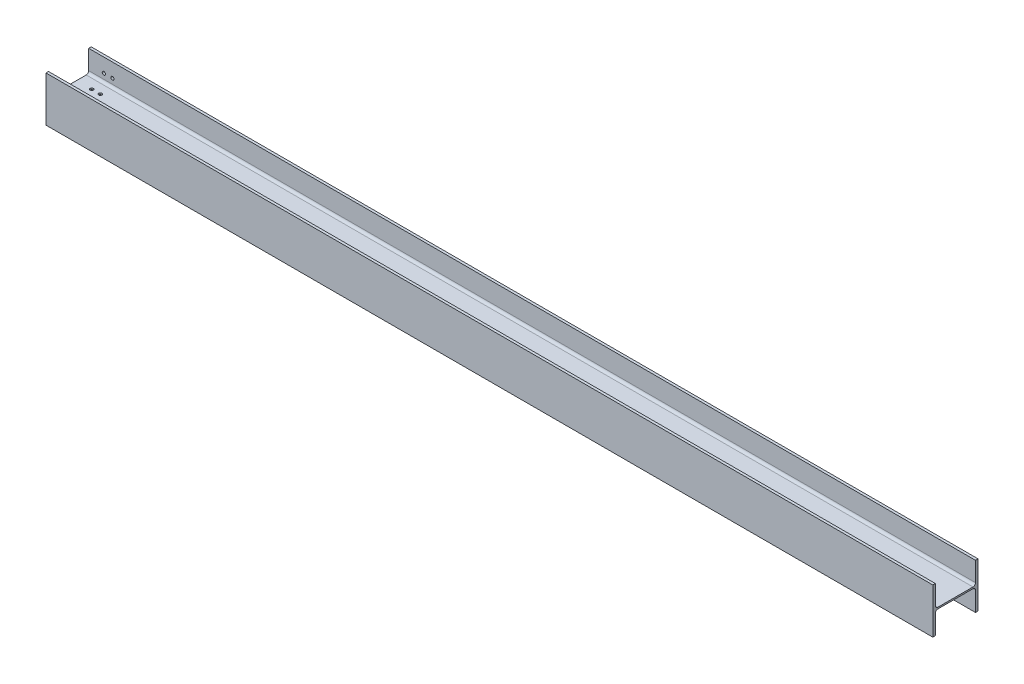
SolidWorks part; units mm, degrees
material "AISI 304 [Custom]"
ref_plane "Front" through (0, 0, 0) normal (0, 0, 1) x (1, 0, 0)
ref_plane "Top" through (0, 0, 0) normal (0, 1, 0) x (1, 0, 0)
ref_plane "Right" through (0, 0, 0) normal (1, 0, 0) x (0, 0, -1)
sketch3d "3DSketch1"
  line L0 (0, 0, 0) -> (-5000, 0, 0) construction
  line L1 (0, 0, 0) -> (-5000, 0, 0)
other "Universal Column_ics 250UC72.9(1)"
ref_plane "Plane1" through (0, 0, 0) normal (-1, 0, 0) x (0, 1, 0)
sketch "Sketch1" plane through (0, 0, 0) normal (-1, 0, 0) x (0, 1, 0)
  line L0 (0, -127) -> (0, 127) construction
  line L1 (-127, -127) -> (127, -127)
  line L2 (127, -127) -> (127, -112.8)
  line L3 (-127, -127) -> (-127, -112.8)
  line L4 (127, -112.8) -> (18.3, -112.8)
  line L5 (-127, -112.8) -> (-18.3, -112.8)
  line L6 (4.3, -98.8) -> (4.3, 98.8)
  line L7 (-4.3, -98.8) -> (-4.3, 98.8)
  line L8 (-127, 112.8) -> (-18.3, 112.8)
  line L9 (-4.3, 0) -> (4.3, 0) construction
  line L10 (127, 112.8) -> (18.3, 112.8)
  line L11 (-127, 127) -> (-127, 112.8)
  line L12 (127, 127) -> (127, 112.8)
  line L13 (-127, 127) -> (127, 127)
  line L14 (127, 112.8) -> (127, -112.8) construction
  line L15 (-127, 112.8) -> (-127, -112.8) construction
  arc A2 (18.3, -112.8) -> (4.3, -98.8) centre (18.3, -98.8) cw
  arc A3 (-18.3, -112.8) -> (-4.3, -98.8) centre (-18.3, -98.8) ccw
  arc A4 (-18.3, 112.8) -> (-4.3, 98.8) centre (-18.3, 98.8) cw
  arc A5 (18.3, 112.8) -> (4.3, 98.8) centre (18.3, 98.8) ccw
  point P6 (0, 0)
  point P9 (127, 0)
  point P10 (-127, 0)
  point P27 (0, 0)
  dimension "R1" = 14
  dimension "Width" = 254
  dimension "Web" = 8.6
  dimension "Height" = 254
  dimension "Flange" = 14.2
extrude "Cut-Extrude2" cut sketch "Sketch3" against normal blind 14.2
sketch "Sketch3" plane through (-4890.5, 0, -127) normal (0, 0, -1) x (0, -1, 0)
  circle A2 centre (48, -33.5) radius 9
  circle A4 centre (48, 14.5) radius 9
  circle A6 centre (-48, -33.5) radius 9
  circle A8 centre (-48, 14.5) radius 9
extrude "Cut-Extrude19" cut sketch "Sketch20" against normal mid plane 8.6
sketch "Sketch20" plane through (-4890.5, 0, 0) normal (0, 1, 0) x (0, 0, -1)
  circle A2 centre (45, -33.5) radius 9
  circle A4 centre (-45, -33.5) radius 9
  circle A6 centre (45, 14.5) radius 9
  circle A8 centre (-45, 14.5) radius 9
extrude "Cut-Extrude20" cut sketch "Sketch21" against normal blind 10
sketch "Sketch21" plane through (-5000, 0, 0) normal (-1, 0, 0) x (0, 1, 0)
  line L8 (127, 127) -> (-127, 127)
  line L9 (127, -127) -> (127, 127)
  line L10 (-127, -127) -> (127, -127)
  line L11 (-127, 127) -> (-127, -127)
extrude "Cut-Extrude21" cut sketch "Sketch22" along normal blind 10
sketch "Sketch22" plane through (0, 0, 0) normal (-1, 0, 0) x (0, 1, 0)
  line L8 (141, 141) -> (-141, 141)
  line L9 (141, -141) -> (141, 141)
  line L10 (-141, -141) -> (141, -141)
  line L11 (-141, 141) -> (-141, -141)
